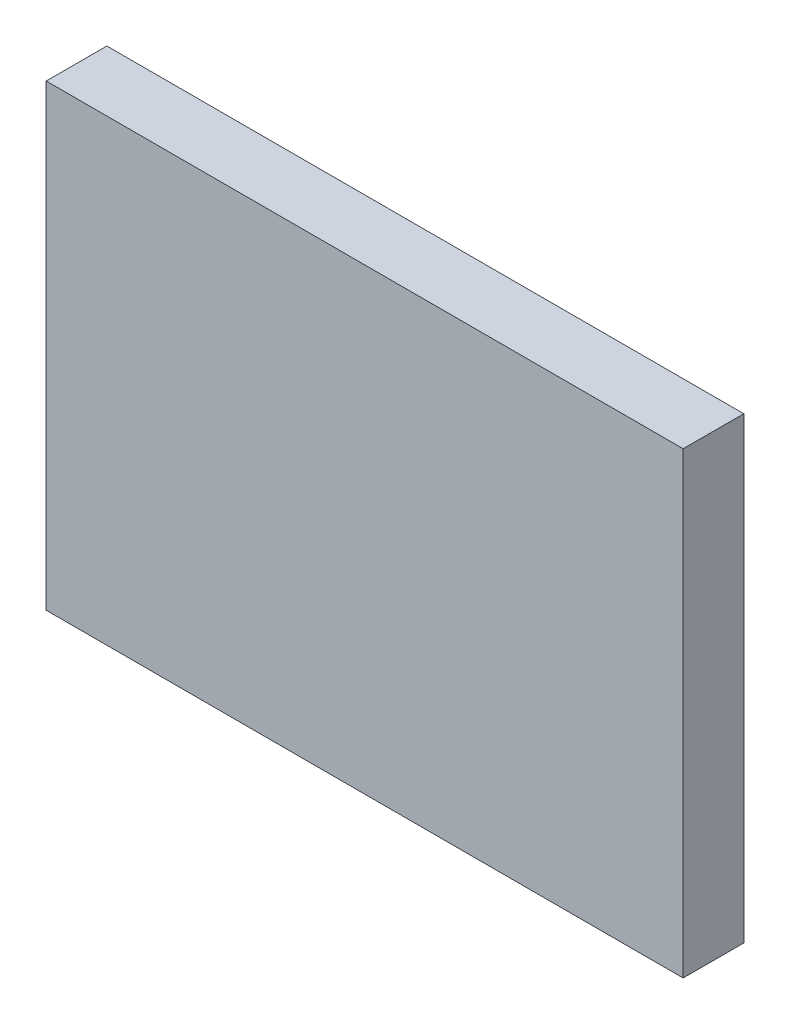
SolidWorks part; units mm, degrees
ref_plane "Front Plane" through (0, 0, 0) normal (0, 0, 1) x (1, 0, 0)
ref_plane "Top Plane" through (0, 0, 0) normal (0, 1, 0) x (1, 0, 0)
ref_plane "Right Plane" through (0, 0, 0) normal (1, 0, 0) x (0, 0, -1)
sketch "Sketch1" plane through (0, 0, 0) normal (0, 0, 1) x (1, 0, 0)
  line B0 (66.7, 0) -> (66.7, 48)
  line B1 (66.7, 48) -> (0, 48)
  line B2 (0, 48) -> (0, 0)
  line B3 (0, 0) -> (66.7, 0)
sketch_block_instance "Back-1"
sketch_block "Back"
extrude "Boss-Extrude1" add sketch "Sketch1" along normal blind 6.35
